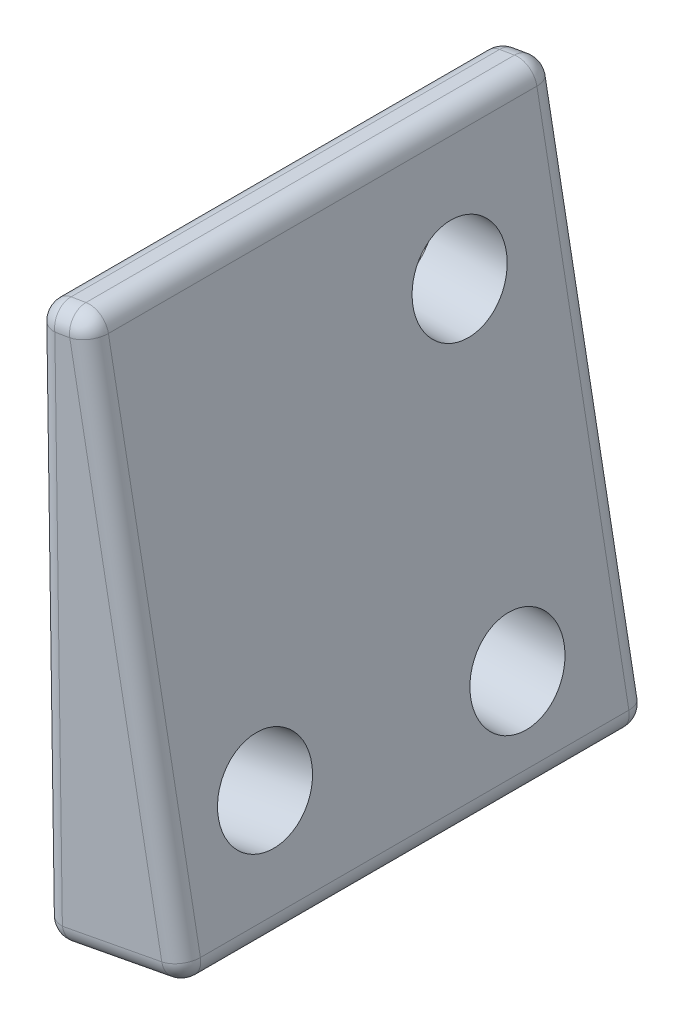
SolidWorks part; units mm, degrees
ref_plane "Front Plane" through (0, 0, 0) normal (0, 0, 1) x (1, 0, 0)
ref_plane "Top Plane" through (0, 0, 0) normal (0, 1, 0) x (1, 0, 0)
ref_plane "Right Plane" through (0, 0, 0) normal (1, 0, 0) x (0, 0, -1)
sketch "Sketch1" plane through (0, 0, 0) normal (0, 0, 1) x (1, 0, 0)
  line L0 (-5.755, -1.093) -> (-6.0854, 21.3485)
  line L2 (0, 0) -> (-5.755, -1.093)
  line L5 (-16.5576, 19.5705) -> (-4.0353, 21.6966) construction
  line L6 (-6.0854, 21.3485) -> (-4.0353, 21.6966)
  line L8 (-4.0353, 21.6966) -> (0, 0)
  line L9 (-6.5226, 51.0413) -> (-4.9335, -56.897) construction
  line L13 (-12.2661, -2.4101) -> (-1.6792, -0.2685) construction
  line L14 (-4.9335, -56.897) -> (-6.5226, 51.0413) construction
  point P2 (0, 0)
  point P3 (0, 0)
  point P4 (-6.0181, -1.2162)
extrude "Boss-Extrude1" add sketch "Sketch1" along normal mid plane 19.05
sketch "Sketch6" plane through (-5.7699, -0.0849, 0) normal (-0.9999, -0.0147, 0) x (0, 0, 1)
  line L1 (-4.7625, 16.5638) -> (-4.7625, 21.4357) construction
  line L2 (-4.7625, 3.8638) -> (-4.7625, -1.0082) construction
  line L3 (9.525, -1.0082) -> (-9.525, -1.0082) construction
  line L4 (-9.525, 21.4357) -> (-9.525, -1.0082) construction
  line L5 (9.525, 21.4357) -> (-9.525, 21.4357) construction
  circle A0 centre (-4.7625, 3.8638) radius 1.905
  circle A1 centre (-4.7625, 16.5638) radius 1.905
  dimension "D2" = 3.81
  dimension "D1" = 12.7
  dimension "D3" = 4.7625
extrude "Cut-Extrude2" cut sketch "Sketch6" against normal through all
sketch "Sketch7" plane through (0, 0, 0) normal (0.9831, 0.1829, 0) x (0, 0, -1)
  circle A0 centre (-5.3786, 4.7186) radius 1.905
  arc A2 (-7.4786, 4.7186) -> (-3.2786, 4.7186) centre (-5.3786, 4.7186) ccw construction
  point P2 (-5.5264, 4.8026)
  point P8 (-4.7625, 6.0892)
  point P9 (0, 0)
  point P10 (-4.7625, 4.9262)
  dimension "D1" = 3.81
extrude "Cut-Extrude3" cut sketch "Sketch7" against normal through all
fillet "Fillet1" radius 0.7937 12 edges at (-2.8775, -0.5465, 9.525) (-5.0604, 21.5225, 9.525) (-4.0353, 21.6966, 0) (-5.0604, 21.5225, -9.525) (-2.0176, 10.8483, 9.525) (0, 0, 0) (-2.8775, -0.5465, -9.525) (-2.0176, 10.8483, -9.525) (-5.9202, 10.1277, 9.525) (-5.755, -1.093, 0) (-5.9202, 10.1277, -9.525) (-6.0854, 21.3485, 0)
